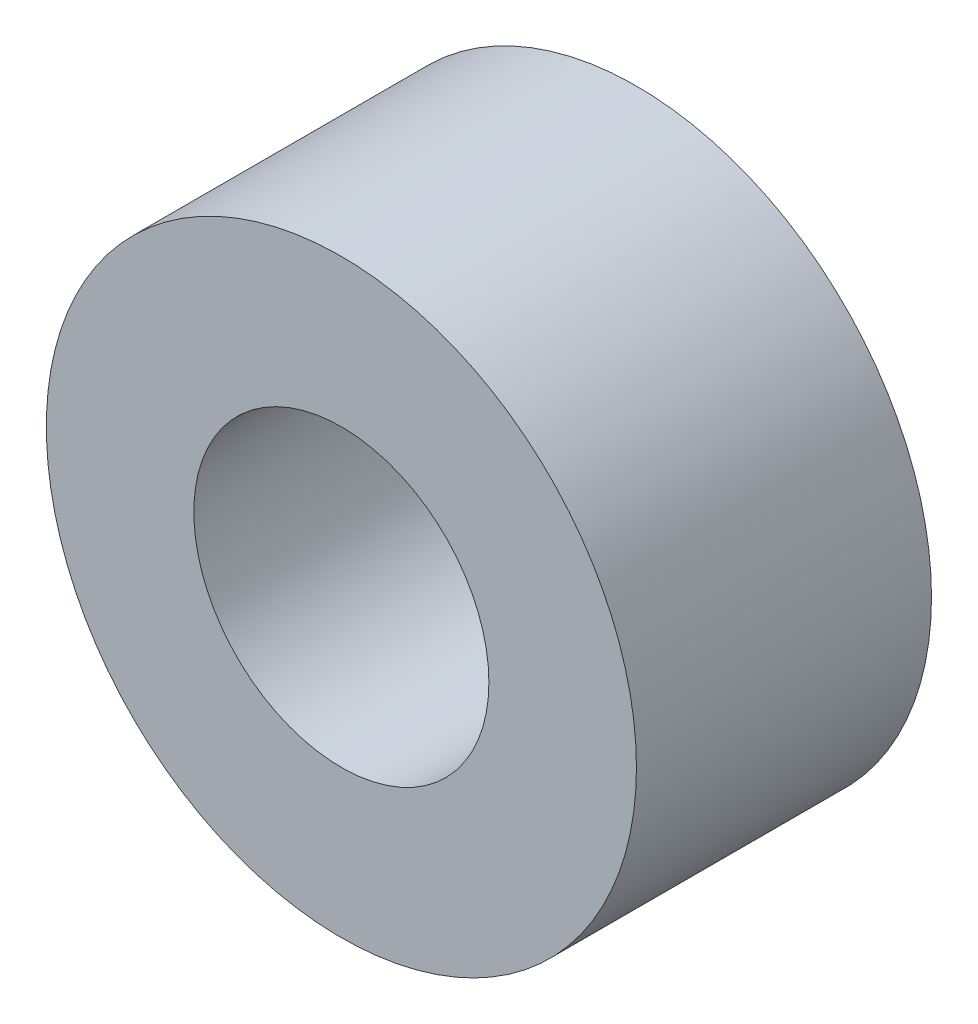
SolidWorks part; units mm, degrees
material "Nylon 101"
ref_plane "Front Plane" through (0, 0, 0) normal (0, 0, 1) x (1, 0, 0)
ref_plane "Top Plane" through (0, 0, 0) normal (0, 1, 0) x (1, 0, 0)
ref_plane "Right Plane" through (0, 0, 0) normal (1, 0, 0) x (0, 0, -1)
sketch "Sketch1" plane through (0, 0, 0) normal (0, 0, 1) x (1, 0, 0)
  circle A0 centre (0, 0) radius 6.35
  circle A1 centre (0, 0) radius 12.7
  dimension "D1" = 12.7
  dimension "D2" = 25.4
extrude "Boss-Extrude1" add sketch "Sketch1" along normal mid plane 12.7
